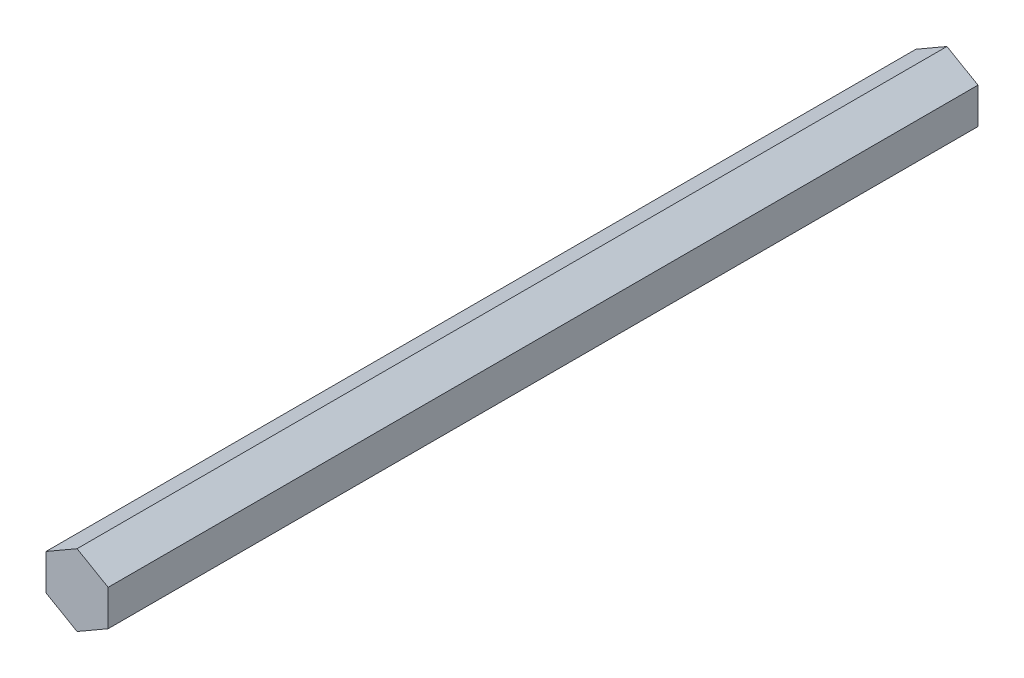
SolidWorks part; units mm, degrees
material "AISI 1020"
ref_plane "Front Plane" through (0, 0, 0) normal (0, 0, 1) x (1, 0, 0)
ref_plane "Top Plane" through (0, 0, 0) normal (0, 1, 0) x (1, 0, 0)
ref_plane "Right Plane" through (0, 0, 0) normal (1, 0, 0) x (0, 0, -1)
sketch "Sketch1" plane through (0, 0, 0) normal (0, 0, 1) x (1, 0, 0)
  line L1 (0, 7.3323) -> (-6.35, 3.6662)
  line L2 (-6.35, 3.6662) -> (-6.35, -3.6662)
  line L3 (-6.35, -3.6662) -> (0, -7.3323)
  line L4 (0, -7.3323) -> (6.35, -3.6662)
  line L5 (6.35, -3.6662) -> (6.35, 3.6662)
  line L6 (6.35, 3.6662) -> (0, 7.3323)
  circle A0 centre (0, 0) radius 6.35 construction
  dimension "D1" = 12.7
extrude "Boss-Extrude1" add sketch "Sketch1" along normal blind 177.8
